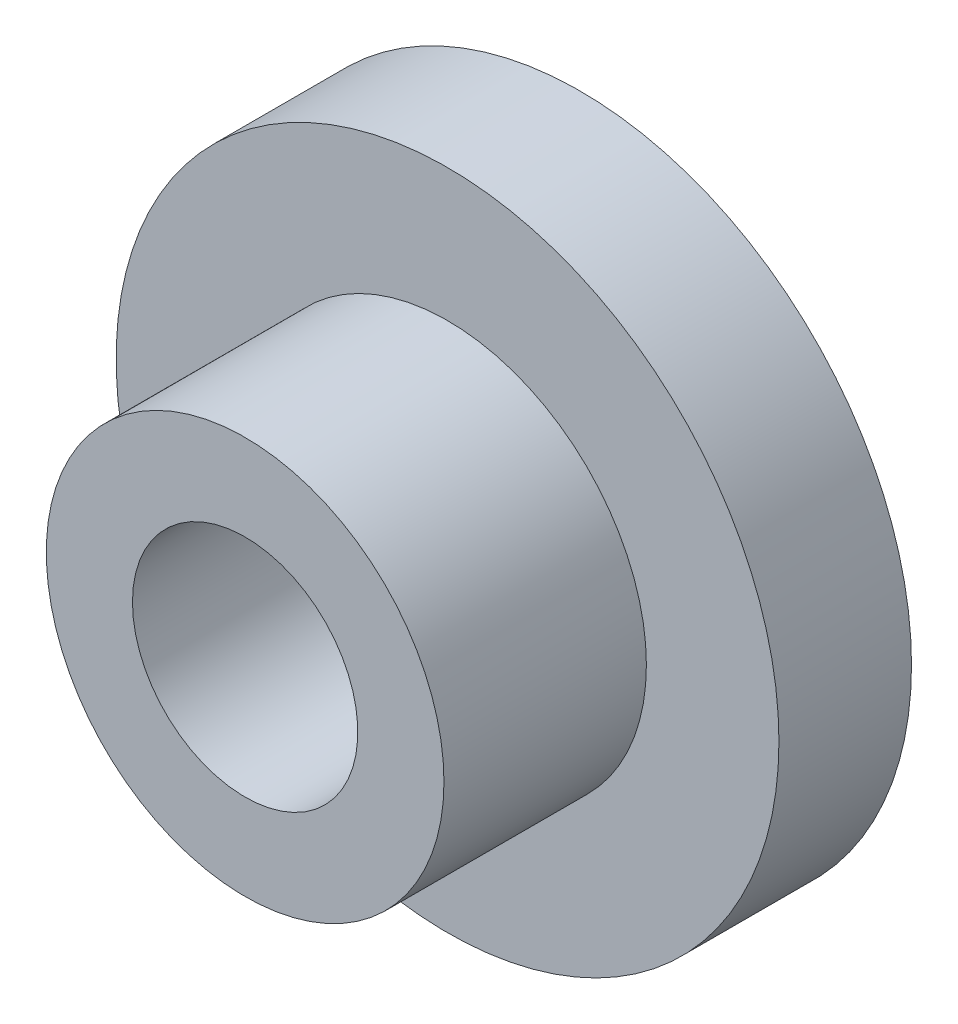
SolidWorks part; units mm, degrees
ref_plane "Front" through (0, 0, 0) normal (0, 0, 1) x (1, 0, 0)
ref_plane "Top" through (0, 0, 0) normal (0, 1, 0) x (1, 0, 0)
ref_plane "Right" through (0, 0, 0) normal (1, 0, 0) x (0, 0, -1)
sketch "Эскиз1" plane through (0, 0, 0) normal (0, 0, 1) x (1, 0, 0)
  circle A1 centre (-15.5, 15.5) radius 3
sketch "Эскиз3" plane through (0, 0, -0.0539) normal (0, 0, 1) x (1, 0, 0)
  circle A0 centre (-15.5, 15.5) radius 5
extrude "Бобышка-Вытянуть2" add sketch "Эскиз1" along normal blind 5 contours A1
extrude "Бобышка-Вытянуть3" add sketch "Эскиз3" along normal blind 2 contours A0
hole_wizard "Отверстие с зазором M31" positions "Эскиз4" profile "Эскиз5" hole size "M3" standard "Ansi Metric" end condition through all
sketch "Эскиз4" plane through (-3.7822, -3.0254, -0.0539) normal (0, 0, -1) x (-0.9756, 0.2196, 0)
  point P0 (15.5, 15.5)
sketch "Эскиз5" plane through (-15.5, 15.5, -0.0539) normal (1, 0, 0) x (0, 1, 0)
  line L0 (0, 0) -> (0, 5.0539)
  line L1 (0, 5.0539) -> (1.7, 5.0539)
  line L2 (1.7, 5.0539) -> (1.7, 0)
  line L3 (1.7, 0) -> (0, 0)
  line L4 (0, -6.35) -> (0, 107.95) construction
  dimension "Диаметр сквозного отверстия" = 3.4
  dimension "Глубина сквозного отверстия" = 5.0539
